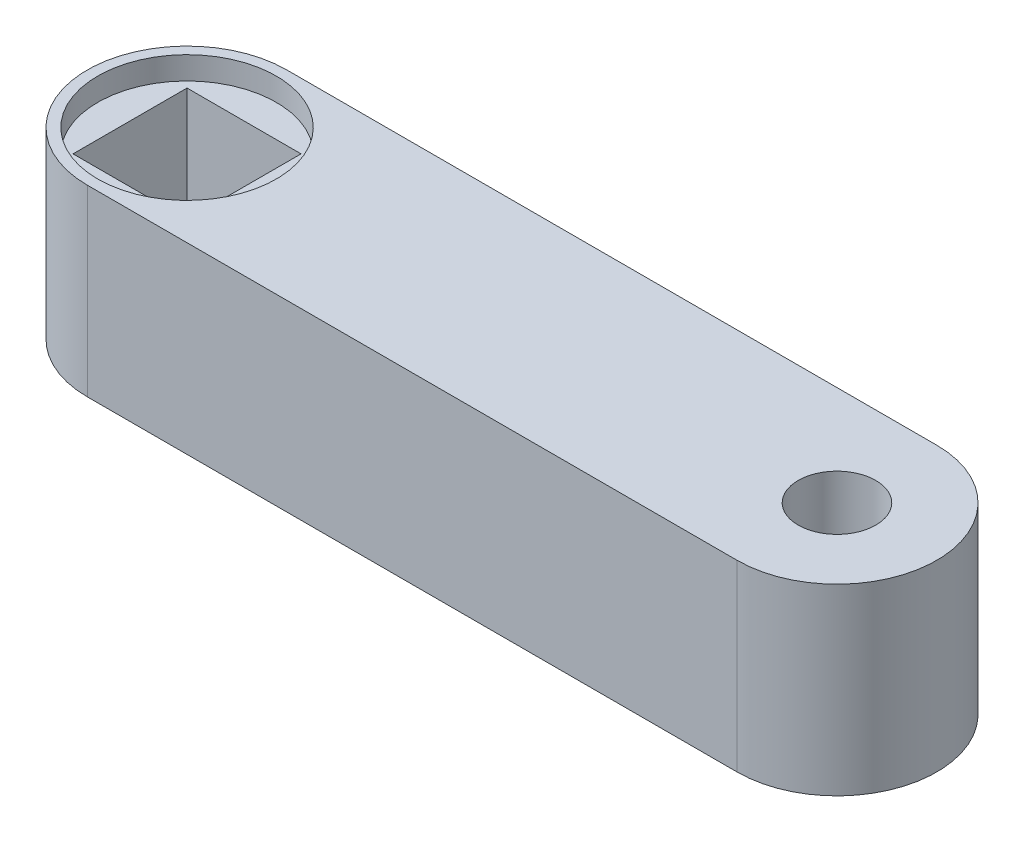
SolidWorks part; units mm, degrees
ref_plane "Front Plane" through (0, 0, 0) normal (0, 0, 1) x (1, 0, 0)
ref_plane "Top Plane" through (0, 0, 0) normal (0, 1, 0) x (1, 0, 0)
ref_plane "Right Plane" through (0, 0, 0) normal (1, 0, 0) x (0, 0, -1)
sketch "Sketch1" plane through (0, 0, 0) normal (0, 1, 0) x (1, 0, 0)
  line L0 (0, 0) -> (36.195, 0) construction
  line L1 (0, 5.5563) -> (36.195, 5.5563)
  line L2 (0, -5.5563) -> (36.195, -5.5563)
  arc A1 (0, 5.5563) -> (0, -5.5563) centre (0, 0) ccw
  arc A2 (36.195, -5.5563) -> (36.195, 5.5563) centre (36.195, 0) ccw
  point P3 (18.0975, 0)
  dimension "D1" = 11.1125
  dimension "D2" = 36.195
extrude "Boss-Extrude1" add sketch "Sketch1" along normal blind 10.2108
sketch "Sketch2" plane through (0, 10.2108, 0) normal (0, 1, 0) x (1, 0, 0)
  line L1 (-3.175, 3.175) -> (3.175, 3.175)
  line L2 (-3.175, 3.175) -> (-3.175, -3.175)
  line L3 (-3.175, -3.175) -> (3.175, -3.175)
  line L4 (3.175, 3.175) -> (3.175, -3.175)
  line L5 (-3.175, 3.175) -> (3.175, -3.175) construction
  line L6 (-3.175, -3.175) -> (3.175, 3.175) construction
  circle A1 centre (36.195, 0) radius 2.159
  point P0 (0, 0)
  dimension "D2" = 6.35
  dimension "D3" = 4.318
  dimension "D1" = 6.35
  dimension "D4" = 36.195
extrude "Cut-Extrude1" cut sketch "Sketch2" against normal through all
sketch "Sketch3" plane through (0, 10.2108, 0) normal (0, 1, 0) x (1, 0, 0)
  circle A0 centre (0, 0) radius 4.9721
  dimension "D1" = 9.9441
extrude "Cut-Extrude2" cut sketch "Sketch3" against normal blind 1.27
ref_plane "Plane1" through (0, 5.1054, 0) normal (0, 1, 0) x (1, 0, 0)
mirror "Mirror1" about plane through (0, 5.1054, 0) normal (0, 1, 0) of "Cut-Extrude2"
